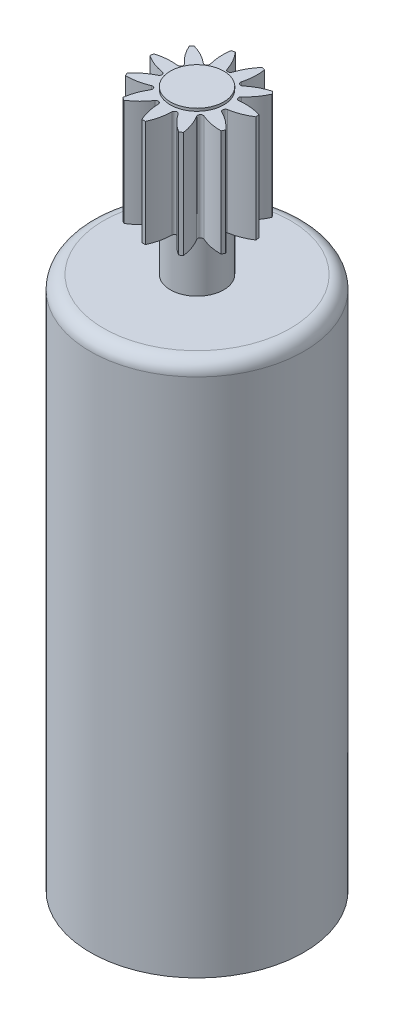
SolidWorks part; units mm, degrees
ref_plane "Front Plane" through (0, 0, 0) normal (0, 0, 1) x (1, 0, 0)
ref_plane "Top Plane" through (0, 0, 0) normal (0, 1, 0) x (1, 0, 0)
ref_plane "Right Plane" through (0, 0, 0) normal (1, 0, 0) x (0, 0, -1)
sketch "Sketch1" plane through (0, 0, 0) normal (0, 0, 1) x (1, 0, 0)
  line L0 (0, 0) -> (0, 26.1)
  line L1 (0, 26.1) -> (1, 26.1)
  line L2 (1, 26.1) -> (1, 26)
  line L3 (1, 26) -> (2, 26)
  line L4 (2, 26) -> (2, 22)
  line L5 (2, 22) -> (1, 22)
  line L6 (1, 22) -> (1, 20)
  line L7 (1, 20) -> (3.5, 20)
  line L8 (4, 19.5) -> (4, 0)
  line L9 (4, 0) -> (0, 0)
  arc A0 (3.5, 20) -> (4, 19.5) centre (3.5, 19.5) cw
  point P13 (4, 20)
  dimension "D9" = 0.5
  dimension "D1" = 26.1
  dimension "D2" = 1
  dimension "D3" = 0.1
  dimension "D4" = 4
  dimension "D5" = 2
  dimension "D6" = 3
  dimension "D7" = 1
  dimension "D8" = 4
revolve "Revolve1" add sketch "Sketch1" angle 360 about L0
sketch "Sketch2" plane through (0, 26, 0) normal (0, 1, 0) x (1, 0, 0)
  line L0 (0, 0) -> (0, 2) construction
  circle A0 centre (0, 0) radius 2 construction
  arc A1 (-0.5, 1.9365) -> (0.5, 1.9365) centre (0, 0) cw
  arc A2 (0.5, 1.9365) -> (0.0953, 1.2198) centre (2.002, 0.6158) ccw
  arc A3 (0.0953, 1.2198) -> (-0.0953, 1.2198) centre (0, 1.25) cw
  arc A4 (-0.5, 1.9365) -> (-0.0953, 1.2198) centre (-2.002, 0.6158) cw
  dimension "D1" = 0.75
  dimension "D3" = 2
  dimension "D4" = 0.1
  dimension "D2" = 1
extrude "Cut-Extrude1" cut sketch "Sketch2" against normal blind 5
pattern_circular "CirPattern1" count 11 over 360 about axis through (0, 0, 0) along (0, 1, 0) of "Cut-Extrude1"
